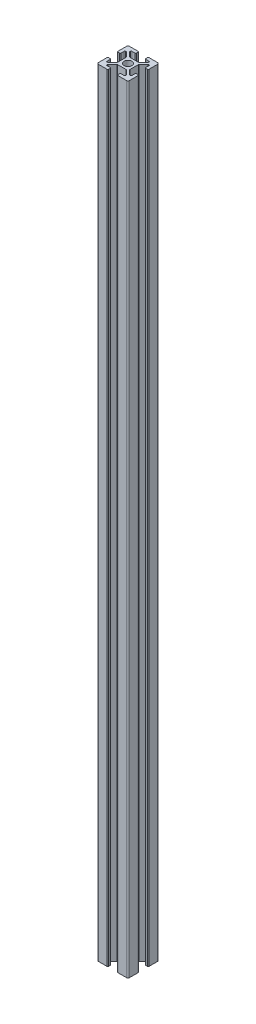
SolidWorks part; units mm, degrees
ref_plane "Front Plane" through (0, 0, 0) normal (0, 0, 1) x (1, 0, 0)
ref_plane "Top Plane" through (0, 0, 0) normal (0, 1, 0) x (1, 0, 0)
ref_plane "Right Plane" through (0, 0, 0) normal (1, 0, 0) x (0, 0, -1)
sketch "Sketch1" plane through (0, 0, 0) normal (0, 1, 0) x (1, 0, 0)
  line L12 (10, 9) -> (10, 3.5)
  line L17 (-10, 10) -> (10, -10) construction
  line L18 (-10, -10) -> (10, 10) construction
  line L20 (8, 5.5) -> (8, 3.5)
  line L26 (3.0858, 4.1464) -> (5.8536, 6.9142)
  line L31 (2.7322, 4) -> (-2.7322, 4)
  line L32 (4, 2.7322) -> (4, -2.7322)
  line L33 (2.7322, -4) -> (-2.7322, -4)
  line L34 (-4, 2.7322) -> (-4, -2.7322)
  line L35 (4, 4) -> (-4, -4) construction
  line L36 (4, -4) -> (-4, 4) construction
  line L37 (0, 0) -> (10, 0) construction
  line L38 (8.5, 3) -> (9.5, 3)
  line L39 (7.2678, 6) -> (7.5, 6)
  line L40 (4.1464, 3.0858) -> (6.9142, 5.8536)
  line L41 (6, 7.2678) -> (6, 7.5)
  line L42 (9, -10) -> (3.5, -10)
  line L43 (8, 8) -> (8, -8) construction
  line L44 (5.5, -8) -> (3.5, -8)
  line L45 (10, 10) -> (10, -10) construction
  line L46 (3, 8.5) -> (3, 9.5)
  line L47 (5.5, 8) -> (3.5, 8)
  line L48 (9, 10) -> (3.5, 10)
  line L49 (-8, 8) -> (8, 8) construction
  line L50 (-10, 10) -> (10, 10) construction
  line L51 (-8, 8) -> (-8, -8) construction
  line L52 (-10, 10) -> (-10, -10) construction
  line L53 (-10, -10) -> (10, -10) construction
  line L54 (-8, -8) -> (8, -8) construction
  line L55 (4.1464, -3.0858) -> (6.9142, -5.8536)
  line L56 (3, -8.5) -> (3, -9.5)
  line L57 (6, -7.2678) -> (6, -7.5)
  line L58 (3.0858, -4.1464) -> (5.8536, -6.9142)
  line L59 (7.2678, -6) -> (7.5, -6)
  line L60 (8.5, -3) -> (9.5, -3)
  line L61 (8, -5.5) -> (8, -3.5)
  line L62 (10, -9) -> (10, -3.5)
  line L63 (-10, -9) -> (-10, -3.5)
  line L64 (-8, -5.5) -> (-8, -3.5)
  line L65 (-3.0858, -4.1464) -> (-5.8536, -6.9142)
  line L66 (-8.5, -3) -> (-9.5, -3)
  line L67 (-7.2678, -6) -> (-7.5, -6)
  line L68 (-4.1464, -3.0858) -> (-6.9142, -5.8536)
  line L69 (-6, -7.2678) -> (-6, -7.5)
  line L70 (-3, -8.5) -> (-3, -9.5)
  line L71 (-5.5, -8) -> (-3.5, -8)
  line L72 (-9, -10) -> (-3.5, -10)
  line L73 (-9, 10) -> (-3.5, 10)
  line L74 (-5.5, 8) -> (-3.5, 8)
  line L75 (-4.1464, 3.0858) -> (-6.9142, 5.8536)
  line L76 (-3, 8.5) -> (-3, 9.5)
  line L77 (-6, 7.2678) -> (-6, 7.5)
  line L78 (-3.0858, 4.1464) -> (-5.8536, 6.9142)
  line L79 (-7.2678, 6) -> (-7.5, 6)
  line L80 (-8.5, 3) -> (-9.5, 3)
  line L81 (-8, 5.5) -> (-8, 3.5)
  line L82 (-10, 9) -> (-10, 3.5)
  circle A1 centre (0, 0) radius 2.5
  arc A2 (7.2678, 6) -> (6.9142, 5.8536) centre (7.2678, 5.5) ccw
  arc A3 (9.5, 3) -> (10, 3.5) centre (9.5, 3.5) ccw
  arc A4 (8.5, 3) -> (8, 3.5) centre (8.5, 3.5) cw
  arc A5 (7.5, 6) -> (8, 5.5) centre (7.5, 5.5) cw
  arc A6 (4, 2.7322) -> (4.1464, 3.0858) centre (4.5, 2.7322) cw
  arc A7 (2.7322, 4) -> (3.0858, 4.1464) centre (2.7322, 4.5) ccw
  arc A8 (6, 7.5) -> (5.5, 8) centre (5.5, 7.5) ccw
  arc A9 (3, 8.5) -> (3.5, 8) centre (3.5, 8.5) ccw
  arc A10 (3, 9.5) -> (3.5, 10) centre (3.5, 9.5) cw
  arc A11 (6, 7.2678) -> (5.8536, 6.9142) centre (5.5, 7.2678) cw
  arc A13 (6, -7.2678) -> (5.8536, -6.9142) centre (5.5, -7.2678) ccw
  arc A14 (3, -9.5) -> (3.5, -10) centre (3.5, -9.5) ccw
  arc A15 (3, -8.5) -> (3.5, -8) centre (3.5, -8.5) cw
  arc A16 (6, -7.5) -> (5.5, -8) centre (5.5, -7.5) cw
  arc A17 (2.7322, -4) -> (3.0858, -4.1464) centre (2.7322, -4.5) cw
  arc A18 (4, -2.7322) -> (4.1464, -3.0858) centre (4.5, -2.7322) ccw
  arc A19 (7.5, -6) -> (8, -5.5) centre (7.5, -5.5) ccw
  arc A20 (8.5, -3) -> (8, -3.5) centre (8.5, -3.5) ccw
  arc A21 (9.5, -3) -> (10, -3.5) centre (9.5, -3.5) cw
  arc A22 (7.2678, -6) -> (6.9142, -5.8536) centre (7.2678, -5.5) cw
  arc A23 (-7.2678, -6) -> (-6.9142, -5.8536) centre (-7.2678, -5.5) ccw
  arc A24 (-9.5, -3) -> (-10, -3.5) centre (-9.5, -3.5) ccw
  arc A25 (-8.5, -3) -> (-8, -3.5) centre (-8.5, -3.5) cw
  arc A26 (-7.5, -6) -> (-8, -5.5) centre (-7.5, -5.5) cw
  arc A27 (-4, -2.7322) -> (-4.1464, -3.0858) centre (-4.5, -2.7322) cw
  arc A28 (-2.7322, -4) -> (-3.0858, -4.1464) centre (-2.7322, -4.5) ccw
  arc A29 (-6, -7.5) -> (-5.5, -8) centre (-5.5, -7.5) ccw
  arc A30 (-3, -8.5) -> (-3.5, -8) centre (-3.5, -8.5) ccw
  arc A31 (-3, -9.5) -> (-3.5, -10) centre (-3.5, -9.5) cw
  arc A32 (-6, -7.2678) -> (-5.8536, -6.9142) centre (-5.5, -7.2678) cw
  arc A33 (-6, 7.2678) -> (-5.8536, 6.9142) centre (-5.5, 7.2678) ccw
  arc A34 (-3, 9.5) -> (-3.5, 10) centre (-3.5, 9.5) ccw
  arc A35 (-3, 8.5) -> (-3.5, 8) centre (-3.5, 8.5) cw
  arc A36 (-6, 7.5) -> (-5.5, 8) centre (-5.5, 7.5) cw
  arc A37 (-2.7322, 4) -> (-3.0858, 4.1464) centre (-2.7322, 4.5) cw
  arc A38 (-4, 2.7322) -> (-4.1464, 3.0858) centre (-4.5, 2.7322) ccw
  arc A39 (-7.5, 6) -> (-8, 5.5) centre (-7.5, 5.5) ccw
  arc A40 (-8.5, 3) -> (-8, 3.5) centre (-8.5, 3.5) ccw
  arc A41 (-9.5, 3) -> (-10, 3.5) centre (-9.5, 3.5) cw
  arc A42 (-7.2678, 6) -> (-6.9142, 5.8536) centre (-7.2678, 5.5) cw
  arc A43 (10, -9) -> (9, -10) centre (9, -9) cw
  arc A44 (-9, -10) -> (-10, -9) centre (-9, -9) cw
  arc A45 (10, 9) -> (9, 10) centre (9, 9) ccw
  arc A46 (-10, 9) -> (-9, 10) centre (-9, 9) cw
  point P0 (0, 0)
  point P144 (0, 0)
  dimension "D3" = 5
  dimension "D7" = 0.5
  dimension "D10" = 0.5
  dimension "D11" = 1
  dimension "D1" = 20
  dimension "D2" = 20
  dimension "D4" = 4
  dimension "D5" = 8
  dimension "D6" = 8
  dimension "D8" = 3
  dimension "D9" = 6
extrude "Boss-Extrude1" add sketch "Sketch1" along normal blind 500
